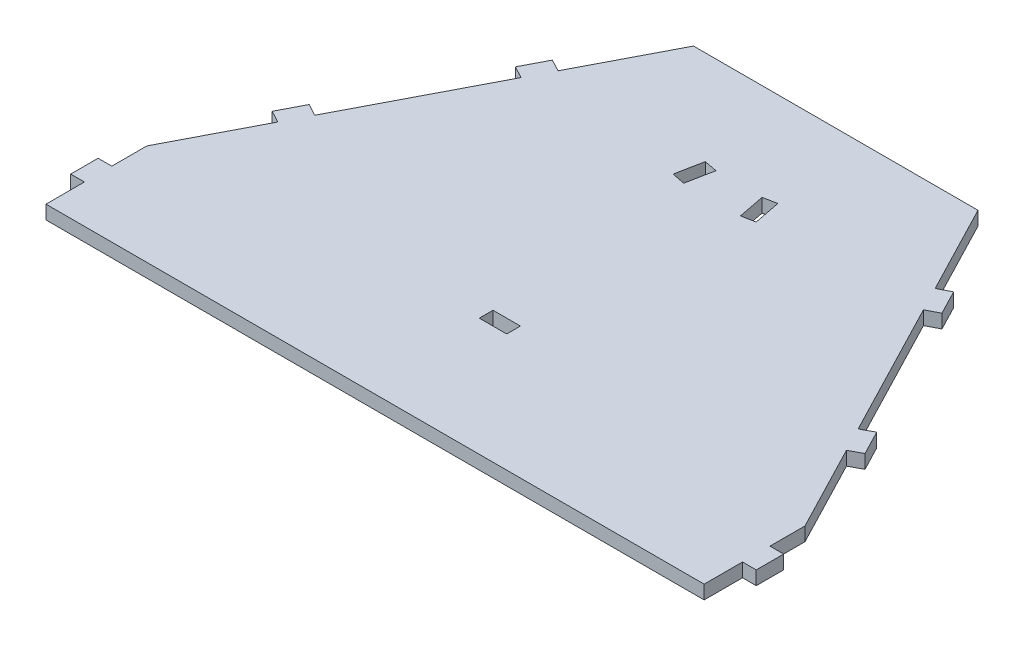
SolidWorks part; units mm, degrees
ref_plane "Front Plane" through (0, 0, 0) normal (0, 0, 1) x (1, 0, 0)
ref_plane "Top Plane" through (0, 0, 0) normal (0, 1, 0) x (1, 0, 0)
ref_plane "Right Plane" through (0, 0, 0) normal (1, 0, 0) x (0, 0, -1)
sketch "Sketch1" plane through (0, 0, 0) normal (0, 1, 0) x (1, 0, 0)
  line L30 (-57.5, 167.9473) -> (57.5, 167.9473)
  line L34 (-57.5, 167.9473) -> (-125, 37.9473)
  line L38 (-125, 37.9473) -> (-125, -0.0527)
  line L39 (-125, -0.0527) -> (125, -0.0527)
  line L40 (125, -0.0527) -> (125, 37.9473)
  line L41 (57.5, 167.9473) -> (125, 37.9473)
  point P0 (0, 167.9473)
  dimension "D1" = 250
  dimension "D2" = 38
  dimension "D3" = 130
  dimension "D4" = 115
  dimension "D5" = 146.4795
  dimension "D6" = 146.4795
  dimension "D7" = 38
extrude "Boss-Extrude1" add sketch "Sketch1" along normal blind 5
sketch "Sketch2" plane through (0, 5, 0) normal (0, 1, 0) x (1, 0, 0)
  line L0 (-103.4765, 79.4) -> (-99.0751, 77.0278)
  line L3 (-125, 23.9473) -> (-120, 23.9473)
  line L5 (-120, 13.9473) -> (-125, 13.9473)
  line L7 (-120, -0.0527) -> (-120, 13.9473)
  line L8 (5, 42.9473) -> (-5, 42.9473)
  line L24 (-125, -0.0527) -> (125, -0.0527) construction
  line L26 (-13.2264, 133.5998) -> (-15.1482, 123.7862)
  line L27 (-78.2497, 127.985) -> (-103.4765, 79.4)
  line L29 (-57.5, 167.9473) -> (-125, 37.9473) construction
  line L33 (-108.0839, 70.5265) -> (-103.6832, 68.1528)
  line L44 (-8.4111, 132.6568) -> (-10.3329, 122.8432)
  line L45 (-5, 42.9473) -> (-5, 47.9473)
  line L46 (-5, 47.9473) -> (5, 47.9473)
  line L47 (5, 47.9473) -> (5, 42.9473)
  line L48 (-13.2264, 133.5998) -> (-8.4111, 132.6568)
  line L49 (-15.1482, 123.7862) -> (-10.3329, 122.8432)
  line L50 (15.1482, 123.7862) -> (10.3329, 122.8432)
  line L51 (13.2264, 133.5998) -> (8.4111, 132.6568)
  line L52 (8.4111, 132.6568) -> (10.3329, 122.8432)
  line L53 (13.2264, 133.5998) -> (15.1482, 123.7862)
  line L54 (-73.8437, 125.6212) -> (-99.0751, 77.0278)
  line L55 (-103.6832, 68.1528) -> (-120, 36.7282)
  line L56 (-68.7427, 135.4431) -> (-51.8655, 167.9473)
  line L57 (57.5, 167.9473) -> (-57.5, 167.9473) construction
  line L62 (-78.2497, 127.985) -> (-77.7889, 128.8725)
  line L67 (-51.8655, 167.9473) -> (-57.5, 167.9473)
  line L68 (-108.0839, 70.5265) -> (-125, 37.9473)
  line L69 (-125, 13.9473) -> (-125, -0.0527)
  line L70 (-120, 23.9473) -> (-120, 36.7282)
  line L82 (-57.5, 167.9473) -> (-73.1807, 137.7474)
  line L83 (-125, 37.9473) -> (-125, 23.9473)
  line L84 (-125, -0.0527) -> (-120, -0.0527)
  line L94 (-73.1807, 137.7474) -> (-68.7427, 135.4431)
  line L95 (-77.7889, 128.8725) -> (-73.3518, 126.5686)
  line L96 (-73.8437, 125.6212) -> (-73.3518, 126.5686)
  line L98 (73.8437, 125.6212) -> (73.3518, 126.5686)
  line L99 (77.7889, 128.8725) -> (73.3518, 126.5686)
  line L100 (73.1807, 137.7474) -> (68.7427, 135.4431)
  line L101 (125, -0.0527) -> (120, -0.0527)
  line L102 (125, 37.9473) -> (125, 23.9473)
  line L103 (57.5, 167.9473) -> (73.1807, 137.7474)
  line L104 (120, 23.9473) -> (120, 36.7282)
  line L105 (125, 13.9473) -> (125, -0.0527)
  line L106 (108.0839, 70.5265) -> (125, 37.9473)
  line L107 (51.8655, 167.9473) -> (57.5, 167.9473)
  line L108 (78.2497, 127.985) -> (77.7889, 128.8725)
  line L109 (68.7427, 135.4431) -> (51.8655, 167.9473)
  line L110 (103.6832, 68.1528) -> (120, 36.7282)
  line L111 (73.8437, 125.6212) -> (99.0751, 77.0278)
  line L112 (108.0839, 70.5265) -> (103.6832, 68.1528)
  line L113 (78.2497, 127.985) -> (103.4765, 79.4)
  line L114 (120, -0.0527) -> (120, 13.9473)
  line L115 (120, 13.9473) -> (125, 13.9473)
  line L116 (125, 23.9473) -> (120, 23.9473)
  line L117 (103.4765, 79.4) -> (99.0751, 77.0278)
  dimension "D13" = 5
  dimension "D4" = 4.9068
  dimension "D5" = 14
  dimension "D6" = 10
  dimension "D7" = 5.0006
  dimension "D8" = 10
  dimension "D1" = 5
  dimension "D9" = 10
  dimension "D10" = 10
  dimension "D11" = 10
  dimension "D12" = 4.9995
  dimension "D15" = 5
  dimension "D16" = 5
  dimension "D17" = 10
  dimension "D18" = 5
  dimension "D19" = 5
  dimension "D20" = 10
  dimension "D24" = 10
  dimension "D25" = 5
  dimension "D26" = 42.9473
  dimension "D33" = 4.9068
extrude "Cut-Extrude1" cut sketch "Sketch2" against normal through all
